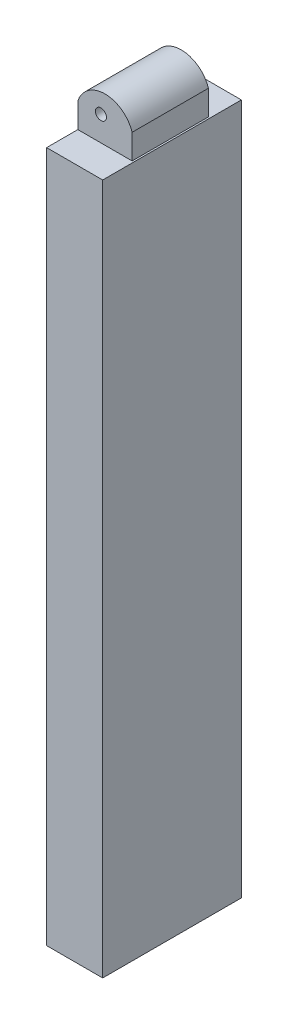
SolidWorks part; units mm, degrees
ref_plane "Front Plane" through (0, 0, 0) normal (1, 0, 0) x (0, 1, 0)
ref_plane "Top Plane" through (0, 0, 0) normal (0, 0, 1) x (0, 1, 0)
ref_plane "Right Plane" through (0, 0, 0) normal (0, 1, 0) x (-1, 0, 0)
sketch "Sketch1" plane through (0, 0, 0) normal (1, 0, 0) x (0, 1, 0)
  line L1 (-59.8, -12) -> (59.8, -12)
  line L2 (-59.8, -12) -> (-59.8, 12)
  line L3 (-59.8, 12) -> (59.8, 12)
  line L4 (59.8, -12) -> (59.8, 12)
  line L5 (-59.8, -12) -> (59.8, 12) construction
  line L6 (-59.8, 12) -> (59.8, -12) construction
  line L7 (49.8, 10) -> (-59.8, 10)
  line L8 (49.8, 10) -> (49.8, -10)
  line L9 (49.8, -10) -> (-59.8, -10)
  line L10 (-59.8, 10) -> (-59.8, -10)
  point P0 (0, 0)
  dimension "D1" = 24
  dimension "D2" = 119.6
  dimension "D3" = 2
  dimension "D4" = 2
  dimension "D5" = 10
extrude "Boss-Extrude1" add sketch "Sketch1" along normal blind 9.7 contours L3 L4 L1 L2
sketch "Sketch3" plane through (0, 59.8, 0) normal (0, 1, 0) x (-1, 0, 0)
  line L1 (-9.4, 6.6) -> (0, 6.6)
  line L2 (-9.4, 6.6) -> (-9.4, -6.6)
  line L3 (-9.4, -6.6) -> (0, -6.6)
  line L4 (0, 6.6) -> (0, -6.6)
  line L5 (0, -12) -> (0, 12) construction
  line L6 (-9.7, -12) -> (0, -12) construction
  line L7 (-9.7, 12) -> (0, 12) construction
  line L9 (-9.7, -12) -> (-9.7, 12) construction
  dimension "D1" = 5.4
  dimension "D2" = 5.4
  dimension "D3" = 0.3
  dimension "D4" = 13.2
extrude "Boss-Extrude2" add sketch "Sketch3" along normal blind 8
sketch "Sketch4" plane through (0, 0, 6.6) normal (0, 0, 1) x (1, 0, 0)
  line L0 (4, 60.1) -> (4, 68.1) construction
  line L9 (0, 59.8) -> (8, 59.8) construction
  line L10 (9.7, 59.8) -> (0, 59.8) construction
  line L14 (0, 59.8) -> (0, 67.5) construction
  line L15 (0, 67.5) -> (8, 67.5) construction
  line L16 (8, 67.5) -> (8, 59.8) construction
  line L18 (-1.4, 64.1) -> (9.4, 64.1) construction
  line L19 (9.4, 67.8) -> (9.4, 59.8) construction
  line L20 (0, 60.1) -> (8, 60.1) construction
  circle A1 centre (4, 64.1) radius 0.95
  arc A3 (0, 64.1) -> (9.4, 64.1) centre (4.7, 62.5515) cw
  point P10 (4, 64.1)
  dimension "D2" = 1.9
  dimension "D1" = 8
  dimension "D3" = 8
  dimension "D4" = 7.7
  dimension "D5" = 0.3
extrude "Cut-Extrude1" cut sketch "Sketch4" against normal through all
